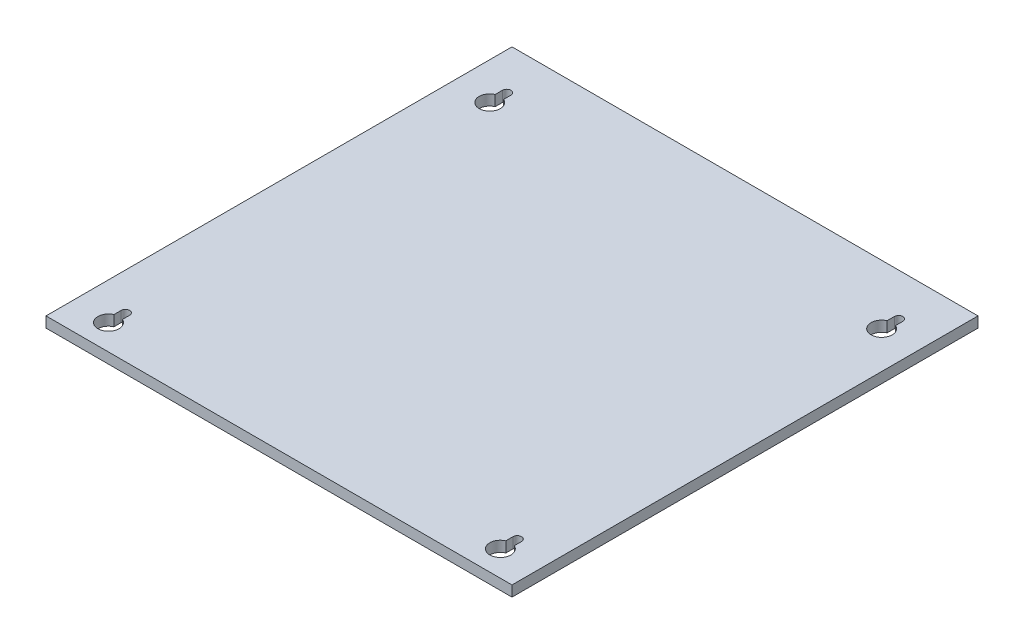
SolidWorks part; units mm, degrees
ref_plane "Front Plane" through (0, 0, 0) normal (0, 0, 1) x (1, 0, 0)
ref_plane "Top Plane" through (0, 0, 0) normal (0, 1, 0) x (1, 0, 0)
ref_plane "Right Plane" through (0, 0, 0) normal (1, 0, 0) x (0, 0, -1)
sketch "Sketch1" plane through (0, 0, 0) normal (0, 1, 0) x (1, 0, 0)
  line L1 (-139.7, -139.7) -> (139.7, -139.7)
  line L2 (-139.7, -139.7) -> (-139.7, 139.7)
  line L3 (-139.7, 139.7) -> (139.7, 139.7)
  line L4 (139.7, -139.7) -> (139.7, 139.7)
  line L5 (-139.7, -139.7) -> (139.7, 139.7) construction
  line L6 (-139.7, 139.7) -> (139.7, -139.7) construction
  point P0 (0, 0)
  dimension "D1" = 279.4
  dimension "D2" = 279.4
extrude "Boss-Extrude1" add sketch "Sketch1" along normal blind 6.35
sketch "Sketch2" plane through (0, 6.35, 0) normal (0, 1, 0) x (1, 0, 0)
  line L0 (-117.475, 114.3) -> (-117.475, 104.14) construction
  line L7 (-117.475, -114.3) -> (117.475, -114.3) construction
  line L9 (-117.475, -114.3) -> (-117.475, 114.3) construction
  line L10 (-117.475, 114.3) -> (117.475, 114.3) construction
  line L11 (117.475, -114.3) -> (117.475, 114.3) construction
  line L12 (-117.475, -114.3) -> (117.475, 114.3) construction
  line L13 (-117.475, 114.3) -> (117.475, -114.3) construction
  line L14 (-114.935, 114.3) -> (-114.935, 109.9599)
  line L15 (-120.015, 114.3) -> (-120.015, 109.9599)
  arc A5 (-114.935, 114.3) -> (-120.015, 114.3) centre (-117.475, 114.3) ccw
  arc A7 (-120.015, 109.9599) -> (-114.935, 109.9599) centre (-117.475, 104.14) ccw
  point P0 (0, 0)
  point P5 (-117.475, 109.22)
  point P6 (0, 0)
  point P8 (-117.475, 104.14)
  point P10 (-119.7157, 110.0815)
  point P11 (-117.475, 116.84)
  point P15 (0, 0)
  point P16 (-114.4725, 109.7353)
  point P18 (0, 0)
  point P19 (-120.3953, 109.7718)
  dimension "D2" = 234.95
  dimension "D3" = 2.54
  dimension "D4" = 12.7
  dimension "D1" = 228.6
  dimension "D5" = 12.7
extrude "Cut-Extrude1" cut sketch "Sketch2" against normal through all
pattern_linear "LPattern1" count 2 spacing 234.95 along (1, 0, 0) count 2 spacing 228.6 along (0, 0, 1) of "Cut-Extrude1"
